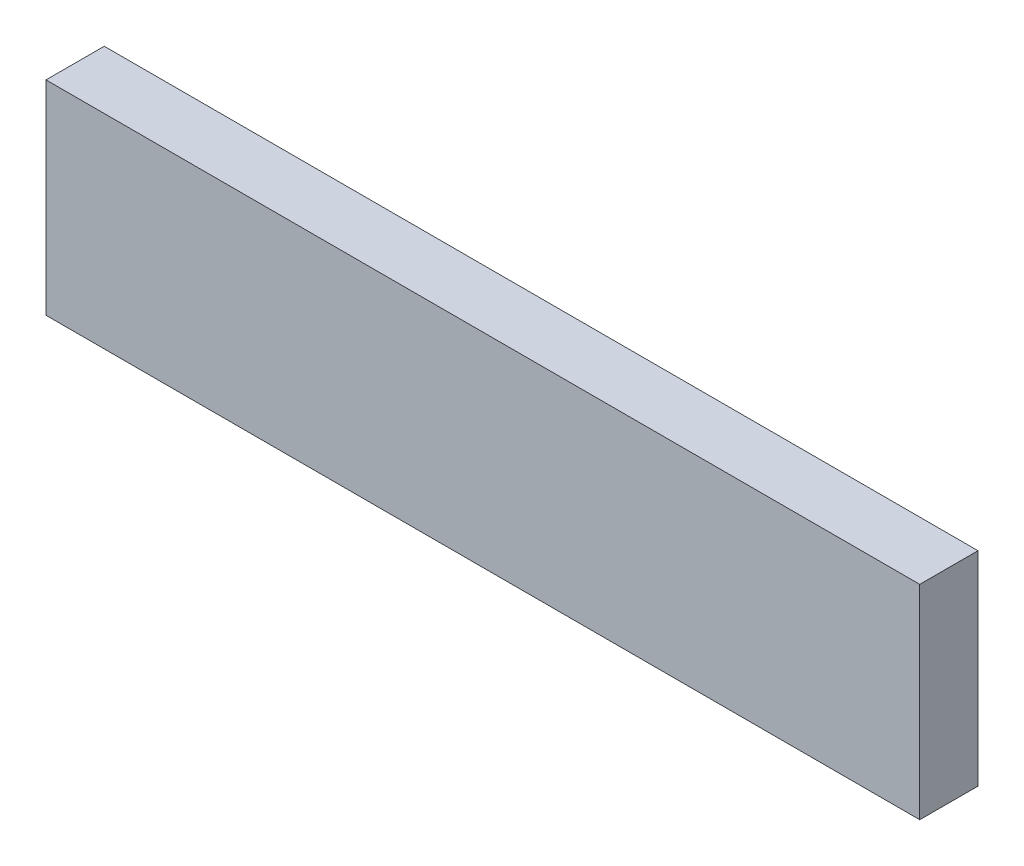
SolidWorks part; units mm, degrees
ref_plane "前视基准面" through (0, 0, 0) normal (0, 0, 1) x (1, 0, 0)
ref_plane "上视基准面" through (0, 0, 0) normal (0, 1, 0) x (1, 0, 0)
ref_plane "右视基准面" through (0, 0, 0) normal (1, 0, 0) x (0, 0, -1)
other "Configuration Table"
sketch "草图1" plane through (0, 0, 0) normal (0, 0, 1) x (1, 0, 0)
  line L1 (-150, -35) -> (150, -35)
  line L2 (-150, -35) -> (-150, 35)
  line L3 (-150, 35) -> (150, 35)
  line L4 (150, -35) -> (150, 35)
  line L5 (-150, -35) -> (150, 35) construction
  line L6 (-150, 35) -> (150, -35) construction
  point P0 (0, 0)
extrude "凸台-拉伸1" add sketch "草图1" along normal blind 20
